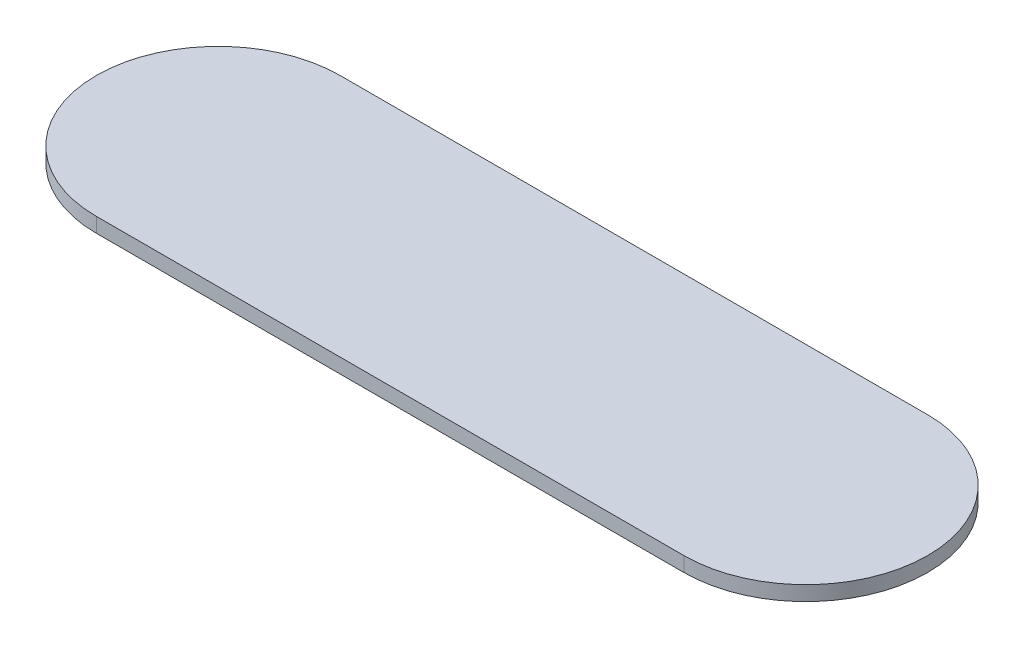
SolidWorks part; units mm, degrees
ref_plane "Front Plane" through (0, 0, 0) normal (0, 0, 1) x (1, 0, 0)
ref_plane "Top Plane" through (0, 0, 0) normal (0, 1, 0) x (1, 0, 0)
ref_plane "Right Plane" through (0, 0, 0) normal (1, 0, 0) x (0, 0, -1)
sketch "Sketch1" plane through (0, 0, 0) normal (0, 1, 0) x (1, 0, 0)
  line L0 (0, 0) -> (100, 0) construction
  line L1 (0, 20.75) -> (100, 20.75)
  line L2 (0, -20.75) -> (100, -20.75)
  arc A0 (0, 20.75) -> (0, -20.75) centre (0, 0) ccw
  arc A1 (100, -20.75) -> (100, 20.75) centre (100, 0) ccw
  point P3 (50, 0)
  dimension "D1" = 20.75
  dimension "D2" = 100
extrude "Boss-Extrude1" add sketch "Sketch1" along normal blind 2.5
sketch "Sketch2" plane through (0, 0, 0) normal (0, -1, 0) x (1, 0, 0)
  line L0 (-20.75, 0) -> (120.75, 0) construction
  circle A0 centre (35, 0) radius 6.25
  circle A1 centre (65, 0) radius 6.25
  arc A2 (0, 20.75) -> (0, -20.75) centre (0, 0) ccw construction
  arc A3 (100, -20.75) -> (100, 20.75) centre (100, 0) ccw construction
  point P14 (65, 0)
  point P15 (35, 0)
  dimension "D1" = 12.5
  dimension "D2" = 12.5
  dimension "D3" = 35
  dimension "D4" = 35
extrude "Cut-Extrude1" cut sketch "Sketch2" against normal blind 1
equation "\"D1@Sketch1\"=41.5/2"
